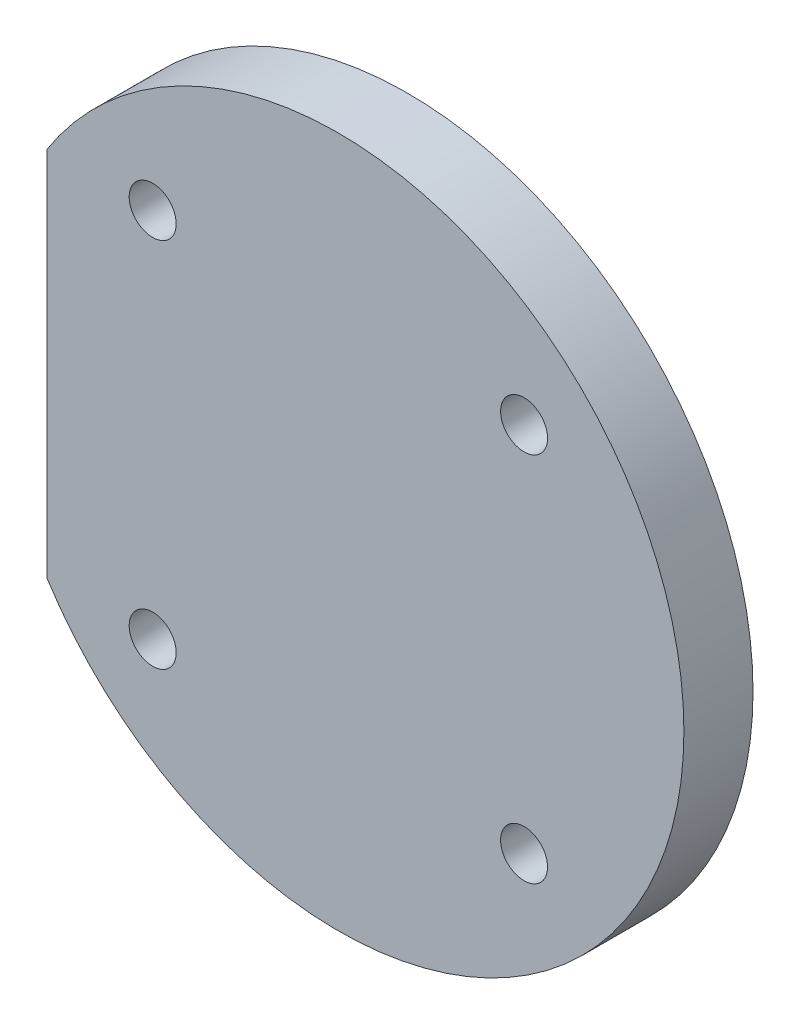
SolidWorks part; units mm, degrees
ref_plane "Plan de face" through (0, 0, 0) normal (0, 0, 1) x (1, 0, 0)
ref_plane "Plan de dessus" through (0, 0, 0) normal (0, 1, 0) x (1, 0, 0)
ref_plane "Plan de droite" through (0, 0, 0) normal (1, 0, 0) x (0, 0, -1)
sketch "Esquisse1" plane through (0, 0, 0) normal (0, 0, 1) x (1, 0, 0)
  circle A0 centre (0, 0) radius 25
  circle A1 centre (-13.435, 13.435) radius 1.7
  circle A2 centre (13.435, 13.435) radius 1.7
  circle A3 centre (13.435, -13.435) radius 1.7
  circle A4 centre (-13.435, -13.435) radius 1.7
  point P19 (0, 0)
  dimension "D1" = 50
  dimension "D5" = 19
  dimension "D6" = 3.4
  dimension "D4" = 4
extrude "Boss.-Extru.1" add sketch "Esquisse1" along normal blind 1 and the other way blind 4
sketch "Esquisse2" plane through (0, 0, -4) normal (0, 0, -1) x (-1, 0, 0)
  line L1 (21.0832, -13.435) -> (28.2033, -13.435)
  line L2 (21.0832, -13.435) -> (21.0832, 13.5101)
  line L3 (21.0832, 13.5101) -> (28.2033, 13.5101)
  line L4 (28.2033, -13.435) -> (28.2033, 13.5101)
  circle A0 centre (0, 0) radius 25 construction
extrude "Enlèv. mat.-Extru.1" cut sketch "Esquisse2" against normal through all
